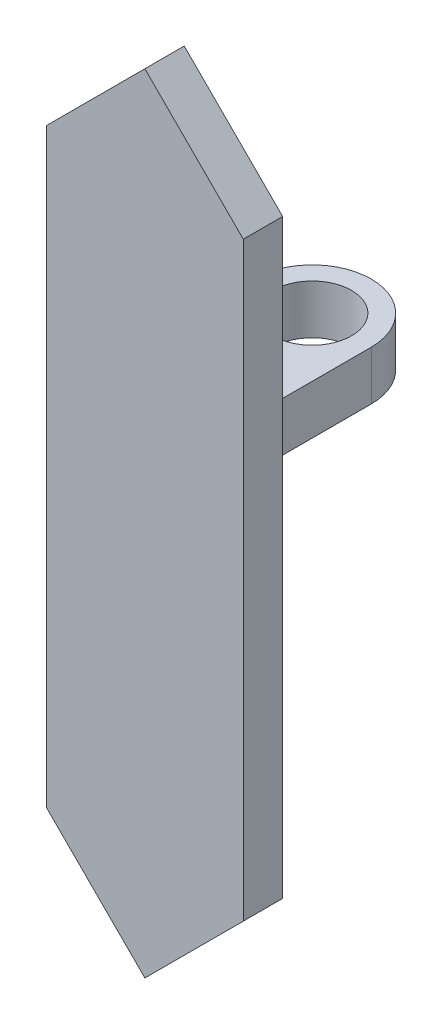
SolidWorks part; units mm, degrees
ref_plane "前视基准面" through (0, 0, 0) normal (0, 0, 1) x (1, 0, 0)
ref_plane "上视基准面" through (0, 0, 0) normal (0, 1, 0) x (1, 0, 0)
ref_plane "右视基准面" through (0, 0, 0) normal (1, 0, 0) x (0, 0, -1)
sketch "草图1" plane through (0, 0, 0) normal (0, 0, 1) x (1, 0, 0)
  line L2 (0.1473, 10) -> (0.1473, 70)
  line L4 (20.1473, 10) -> (20.1473, 70)
  line L5 (0.1473, 70) -> (10.1473, 80)
  line L6 (10.1473, 80) -> (20.1473, 70)
  line L8 (10.1473, 0) -> (20.1473, 10)
  line L9 (0.1473, 10) -> (10.1473, 0)
extrude "凸台-拉伸1" add sketch "草图1" along normal blind 4 contours L2 L9 L8 L4 L6 L5
sketch "草图2" plane through (0, 0, 0) normal (0, 0, -1) x (-1, 0, 0)
  line L0 (-10.1473, 50) -> (-10.1473, 80)
  line L5 (-16.1473, 50) -> (-4.1473, 50)
  line L6 (-16.1473, 50) -> (-16.1473, 45)
  line L7 (-16.1473, 45) -> (-4.1473, 45)
  line L8 (-4.1473, 50) -> (-4.1473, 45)
  line L9 (-16.1473, 50) -> (-4.1473, 45) construction
  line L10 (-16.1473, 45) -> (-4.1473, 50) construction
  point P8 (-10.1473, 47.5)
  dimension "D1" = 30
extrude "凸台-拉伸2" add sketch "草图2" along normal blind 20 contours L8 L5 L6 L7
sketch "草图6" plane through (0, 45, 0) normal (0, -1, 0) x (1, 0, 0)
  line L0 (10.1473, -13) -> (10.1473, 0)
  line L1 (16.1473, 0) -> (4.1473, 0) construction
  circle A0 centre (10.1473, -13) radius 6
  circle A1 centre (10.1473, -13) radius 4
  dimension "D2" = 12
  dimension "D1" = 13
extrude "切除-拉伸5" cut sketch "草图6" against normal blind 21
